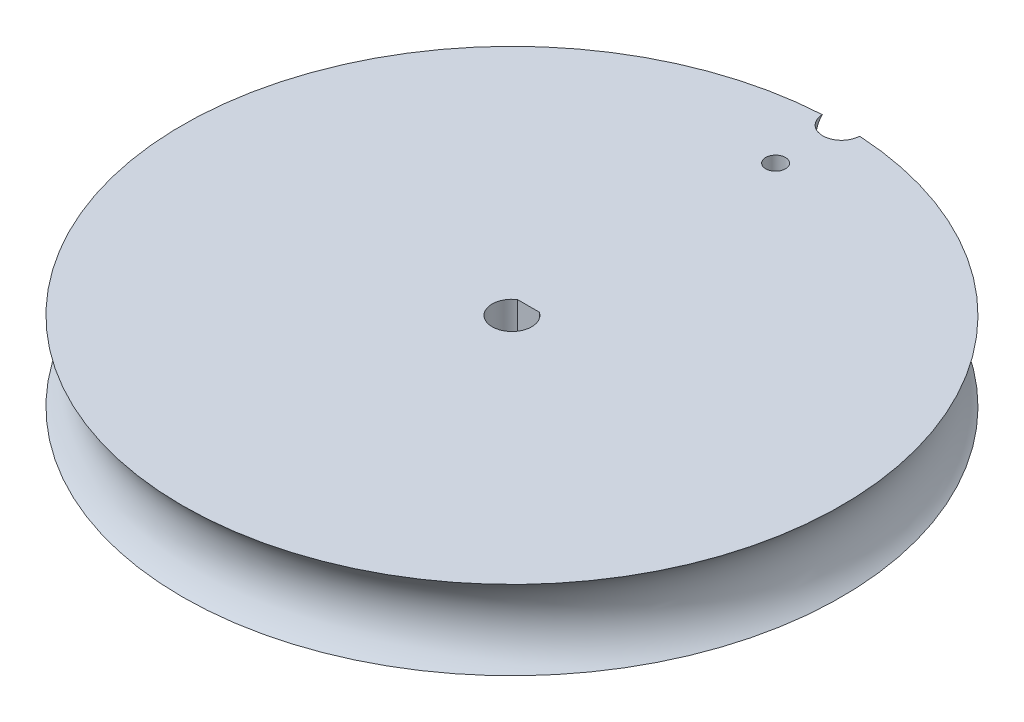
SolidWorks part; units mm, degrees
ref_plane "Front Plane" through (0, 0, 0) normal (0, 0, 1) x (1, 0, 0)
ref_plane "Top Plane" through (0, 0, 0) normal (0, 1, 0) x (1, 0, 0)
ref_plane "Right Plane" through (0, 0, 0) normal (1, 0, 0) x (0, 0, -1)
sketch "Sketch2" plane through (0, 0, 0) normal (0, 1, 0) x (1, 0, 0)
  line L0 (0, -50) -> (0, 50) construction
  line L1 (-1.6583, 2.5) -> (1.6583, 2.5)
  arc A0 (-2.8273, 49.92) -> (2.8273, 49.92) centre (0, 0) ccw
  arc A1 (-1.6583, 2.5) -> (1.6583, 2.5) centre (0, 0) ccw
  circle A2 centre (0, 40) radius 1.5
  arc A3 (2.8273, 49.92) -> (-2.8273, 49.92) centre (0, 50) cw
  point P1 (0, 0)
  point P6 (0, 0)
  point P9 (0, -3)
  point P13 (0, 0)
  point P14 (0, 0)
  point P15 (0, -50)
  point P16 (0, -50)
  point P17 (0, 0)
  point P18 (0, 50)
  point P19 (0, 0)
  point P20 (0, 0)
  point P21 (0, 0)
  point P22 (0, 0)
  point P23 (0, 0)
  point P24 (0, 0)
  dimension "D1" = 100
  dimension "D2" = 6
  dimension "D3" = 5.5
  dimension "D4" = 3
  dimension "D6" = 2.8284
  dimension "D5" = 10
sketch3d "3DSketch1"
  line L0 (0, 0, 50) -> (0, 0, -50) construction
extrude "Boss-Extrude3" add sketch "Sketch2" along normal blind 12 contours A0
sketch "Sketch4" plane through (0, 0, 0) normal (0, 0, 1) x (1, 0, 0)
  line L0 (50, 0) -> (50, 12) construction
  line L1 (-54.8341, 6) -> (45.1659, 6) construction
  line L2 (50, 12) -> (-50, 12) construction
  line L3 (-50, 0) -> (50, 0) construction
  circle A1 centre (55, 6) radius 7.8102
  dimension "D1" = 5
sketch "Sketch6" plane through (0, 0, 0) normal (0, 0, 1) x (1, 0, 0)
  line L0 (0, 0) -> (0, 12) construction
revolve "Cut-Revolve1" cut sketch "Sketch4" angle 360 about L0
